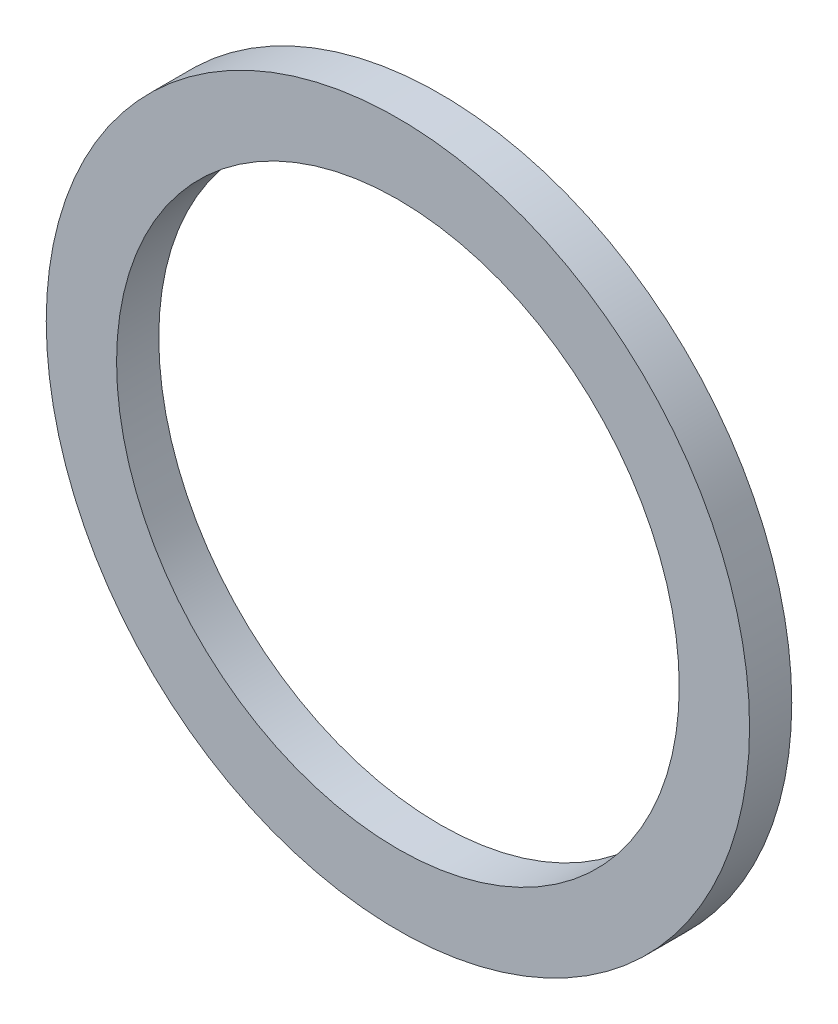
SolidWorks part; units mm, degrees
material "AISI 4130 Steel, normalized at 870C"
ref_plane "Front Plane" through (0, 0, 0) normal (0, 0, 1) x (1, 0, 0)
ref_plane "Top Plane" through (0, 0, 0) normal (0, 1, 0) x (1, 0, 0)
ref_plane "Right Plane" through (0, 0, 0) normal (1, 0, 0) x (0, 0, -1)
sketch "Sketch1" plane through (0, 0, 0) normal (0, 0, 1) x (1, 0, 0)
  circle A0 centre (0, 0) radius 25
  circle A1 centre (0, 0) radius 20
  dimension "D1" = 50
  dimension "D2" = 40
extrude "Boss-Extrude1" add sketch "Sketch1" along normal blind 2
sketch "Sketch2" plane through (0, 0, 2) normal (0, 0, 1) x (1, 0, 0)
  circle A1 centre (0, 0) radius 25
  circle A2 centre (0, 0) radius 25
  dimension "D1" = 0
extrude "Boss-Extrude2" add sketch "Sketch2" along normal blind 1
sketch "Sketch3" plane through (0, 0, 2) normal (0, 0, -1) x (-1, 0, 0)
  circle A1 centre (0, 0) radius 20
  circle A2 centre (0, 0) radius 20
  dimension "D1" = 0
extrude "Cut-Extrude1" cut sketch "Sketch3" against normal blind 1
